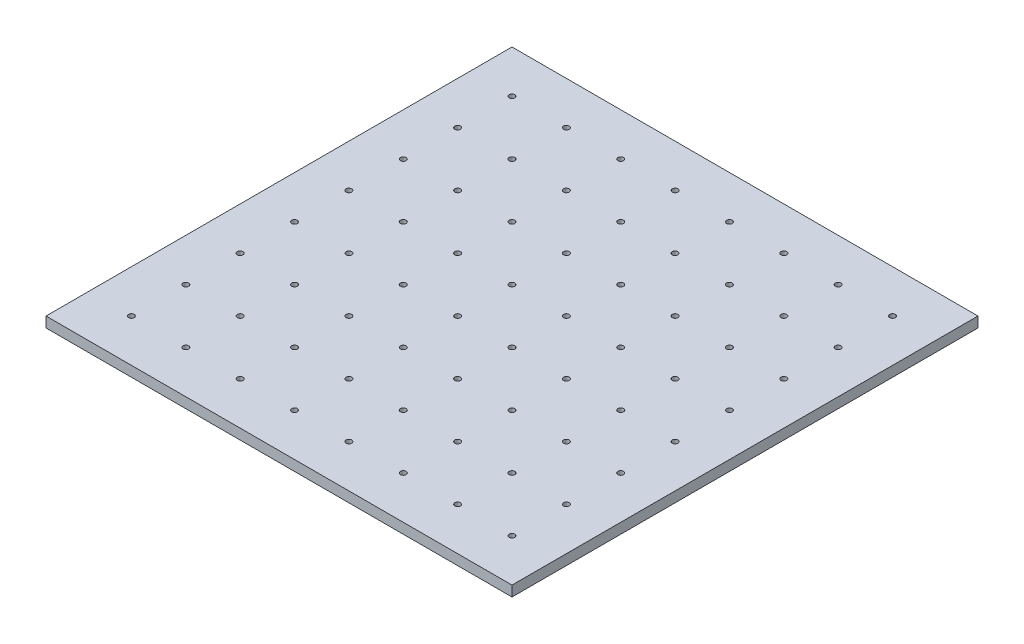
SolidWorks part; units mm, degrees
material "ﾊﾞﾙｻ"
ref_plane "正面" through (0, 0, 0) normal (0, 0, 1) x (1, 0, 0)
ref_plane "平面" through (0, 0, 0) normal (0, 1, 0) x (1, 0, 0)
ref_plane "右側面" through (0, 0, 0) normal (1, 0, 0) x (0, 0, -1)
sketch "ｽｹｯﾁ1" plane through (0, 0, 0) normal (0, 1, 0) x (1, 0, 0)
  line L0 (-10.5, -10.5) -> (10.5, 10.5) construction
  line L1 (90, -90) -> (-90, -90)
  line L2 (90, -90) -> (90, 90)
  line L3 (90, 90) -> (-90, 90)
  line L4 (-90, -90) -> (-90, 90)
  line L5 (90, -90) -> (-90, 90) construction
  line L6 (90, 90) -> (-90, -90) construction
  circle A0 centre (-73.5, 52.5) radius 1.1
  circle A1 centre (-73.5, 73.5) radius 1.1
  circle A2 centre (-52.5, 73.5) radius 1.1
  circle A3 centre (-52.5, 52.5) radius 1.1
  circle A4 centre (-31.5, 52.5) radius 1.1
  circle A5 centre (-31.5, 73.5) radius 1.1
  circle A6 centre (-10.5, 73.5) radius 1.1
  circle A7 centre (-10.5, 52.5) radius 1.1
  circle A8 centre (10.5, 52.5) radius 1.1
  circle A9 centre (10.5, 73.5) radius 1.1
  circle A10 centre (31.5, 73.5) radius 1.1
  circle A11 centre (31.5, 52.5) radius 1.1
  circle A12 centre (52.5, 52.5) radius 1.1
  circle A13 centre (52.5, 73.5) radius 1.1
  circle A14 centre (73.5, 73.5) radius 1.1
  circle A15 centre (73.5, 52.5) radius 1.1
  circle A16 centre (-31.5, 10.5) radius 1.1
  circle A17 centre (-31.5, 31.5) radius 1.1
  circle A18 centre (-10.5, 31.5) radius 1.1
  circle A19 centre (-10.5, 10.5) radius 1.1
  circle A20 centre (10.5, 10.5) radius 1.1
  circle A21 centre (10.5, 31.5) radius 1.1
  circle A22 centre (31.5, 31.5) radius 1.1
  circle A23 centre (31.5, 10.5) radius 1.1
  circle A24 centre (52.5, 10.5) radius 1.1
  circle A25 centre (52.5, 31.5) radius 1.1
  circle A26 centre (73.5, 31.5) radius 1.1
  circle A27 centre (73.5, 10.5) radius 1.1
  circle A28 centre (-31.5, -31.5) radius 1.1
  circle A29 centre (-31.5, -10.5) radius 1.1
  circle A30 centre (-10.5, -10.5) radius 1.1
  circle A31 centre (-10.5, -31.5) radius 1.1
  circle A32 centre (10.5, -31.5) radius 1.1
  circle A33 centre (10.5, -10.5) radius 1.1
  circle A34 centre (31.5, -10.5) radius 1.1
  circle A35 centre (31.5, -31.5) radius 1.1
  circle A36 centre (52.5, -31.5) radius 1.1
  circle A37 centre (52.5, -10.5) radius 1.1
  circle A38 centre (73.5, -10.5) radius 1.1
  circle A39 centre (73.5, -31.5) radius 1.1
  circle A40 centre (-31.5, -73.5) radius 1.1
  circle A41 centre (-31.5, -52.5) radius 1.1
  circle A42 centre (-10.5, -52.5) radius 1.1
  circle A43 centre (-10.5, -73.5) radius 1.1
  circle A44 centre (10.5, -73.5) radius 1.1
  circle A45 centre (10.5, -52.5) radius 1.1
  circle A46 centre (31.5, -52.5) radius 1.1
  circle A47 centre (31.5, -73.5) radius 1.1
  circle A48 centre (52.5, -73.5) radius 1.1
  circle A49 centre (52.5, -52.5) radius 1.1
  circle A50 centre (73.5, -52.5) radius 1.1
  circle A51 centre (73.5, -73.5) radius 1.1
  circle A52 centre (-73.5, 10.5) radius 1.1
  circle A53 centre (-73.5, 31.5) radius 1.1
  circle A54 centre (-52.5, 31.5) radius 1.1
  circle A55 centre (-52.5, 10.5) radius 1.1
  circle A56 centre (-73.5, -31.5) radius 1.1
  circle A57 centre (-73.5, -10.5) radius 1.1
  circle A58 centre (-52.5, -10.5) radius 1.1
  circle A59 centre (-52.5, -31.5) radius 1.1
  circle A60 centre (-73.5, -73.5) radius 1.1
  circle A61 centre (-73.5, -52.5) radius 1.1
  circle A62 centre (-52.5, -52.5) radius 1.1
  circle A63 centre (-52.5, -73.5) radius 1.1
  point P0 (0, 0)
  point P6 (-92.0846, 98.8805)
  point P8 (0, 0)
  point P18 (-63, 63)
  dimension "D3" = 2.2
  dimension "D1" = 4
  dimension "D2" = 21
  dimension "D6" = 21
  dimension "D7" = 21
  dimension "D8" = 180
  dimension "D4" = 4
  dimension "D5" = 4
extrude "ﾎﾞｽ - 押し出し1" add sketch "ｽｹｯﾁ1" along normal blind 4
